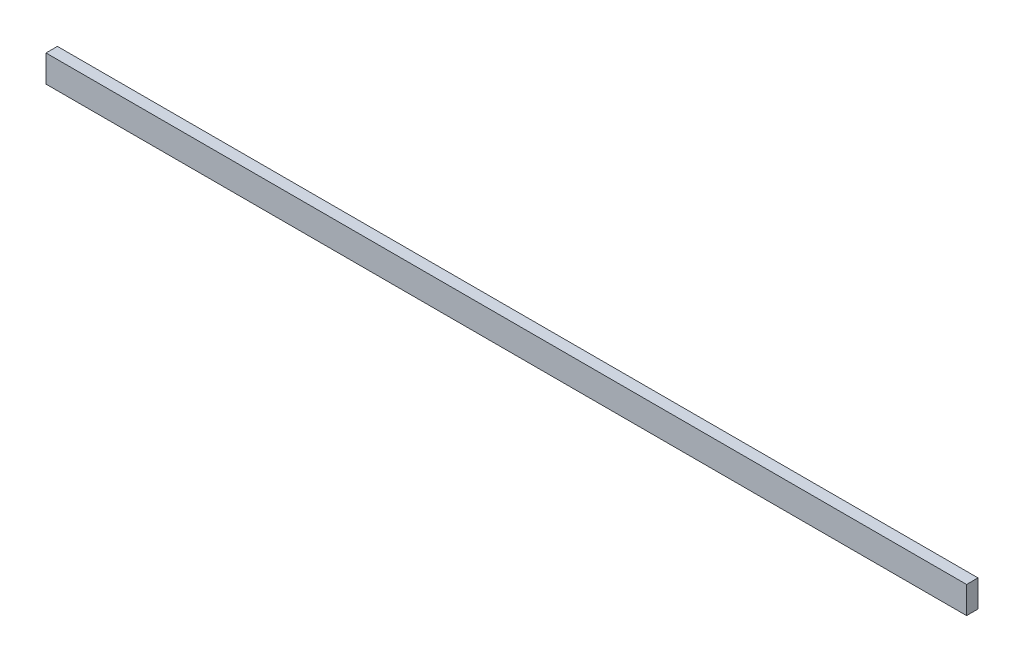
SolidWorks part; units mm, degrees
ref_plane "Front" through (0, 0, 0) normal (0, 0, 1) x (1, 0, 0)
ref_plane "Top" through (0, 0, 0) normal (0, 1, 0) x (1, 0, 0)
ref_plane "Right" through (0, 0, 0) normal (1, 0, 0) x (0, 0, -1)
sketch "Sketch1" plane through (0, 0, 0) normal (0, 1, 0) x (1, 0, 0)
  line L0 (1533.9, 9.75) -> (1533.9, -9.75) construction
  line L1 (1533.9, 9.5) -> (0, 9.5)
  line L2 (1533.9, 9.5) -> (1533.9, -9.5)
  line L3 (1533.9, -9.5) -> (0, -9.5)
  line L4 (0, 9.5) -> (0, -9.5)
  line L5 (1533.9, 9.5) -> (0, -9.5) construction
  line L6 (1533.9, -9.5) -> (0, 9.5) construction
  point P0 (766.95, 0)
  dimension "D1" = 19
extrude "Boss-Extrude1" add sketch "Sketch1" along normal blind 45
